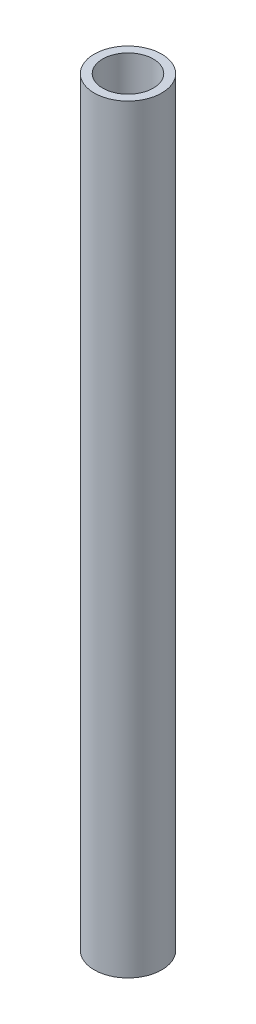
SolidWorks part; units mm, degrees
material "Hexcel AS4C (3000 丝)"
ref_plane "前视基准面" through (0, 0, 0) normal (0, 0, 1) x (1, 0, 0)
ref_plane "上视基准面" through (0, 0, 0) normal (0, 1, 0) x (1, 0, 0)
ref_plane "右视基准面" through (0, 0, 0) normal (1, 0, 0) x (0, 0, -1)
sketch "草图1" plane through (0, 0, 0) normal (0, 1, 0) x (1, 0, 0)
  circle A0 centre (0, 0) radius 2
  circle A1 centre (0, 0) radius 1.5
extrude "凸台-拉伸1" add sketch "草图1" along normal blind 40
sketch "草图2" plane through (0, 40, 0) normal (0, 1, 0) x (1, 0, 0)
  circle A0 centre (0, 0) radius 1.5
  circle A1 centre (0, 0) radius 2
extrude "凸台-拉伸3" add sketch "草图2" along normal blind 5
